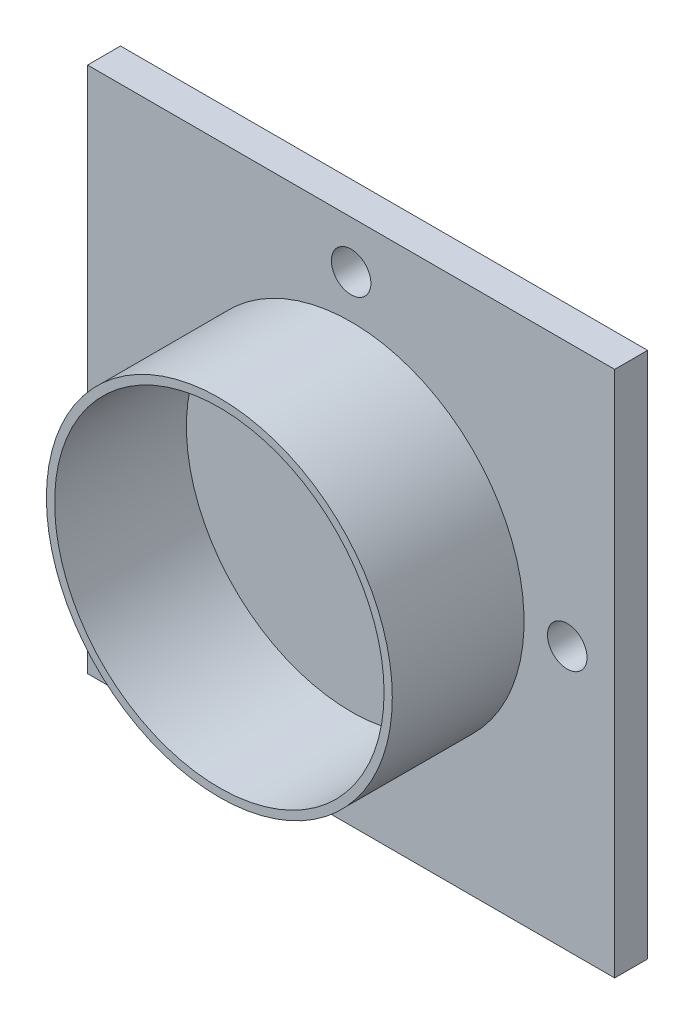
SolidWorks part; units mm, degrees
material "1023 Carbon Steel Sheet (SS)"
ref_plane "Front Plane" through (0, 0, 0) normal (0, 0, 1) x (1, 0, 0)
ref_plane "Top Plane" through (0, 0, 0) normal (0, 1, 0) x (1, 0, 0)
ref_plane "Right Plane" through (0, 0, 0) normal (1, 0, 0) x (0, 0, -1)
sketch "Sketch1" plane through (0, 0, 0) normal (0, 0, 1) x (1, 0, 0)
  line L1 (-39.9048, -160) -> (280.0952, -160)
  line L2 (-39.9048, -160) -> (-39.9048, 160)
  line L3 (-39.9048, 160) -> (280.0952, 160)
  line L4 (280.0952, -160) -> (280.0952, 160)
  line L5 (120.0952, 160) -> (120.0952, -160) construction
  line L6 (-39.9048, 0) -> (280.0952, 0) construction
  point P232 (120.0952, 0)
extrude "Boss-Extrude1" add sketch "Sketch1" along normal blind 20
sketch "Sketch2" plane through (0, 0, 20) normal (0, 0, 1) x (1, 0, 0)
  circle A0 centre (120.0952, 0) radius 105
  circle A1 centre (120.0952, 0) radius 100
  dimension "D1" = 210
  dimension "D2" = 200
extrude "Boss-Extrude2" add sketch "Sketch2" along normal blind 80
sketch "Sketch4" plane through (0, 0, 20) normal (0, 0, 1) x (1, 0, 0)
  circle A0 centre (120.0952, 131.2087) radius 12
  circle A1 centre (251.304, 0) radius 12
  circle A2 centre (120.0952, -131.2087) radius 12
  circle A3 centre (-11.1135, 0) radius 12
  point P11 (120.0952, 0)
  dimension "D1" = 24
  dimension "D2" = 4
extrude "Cut-Extrude1" cut sketch "Sketch4" against normal through all
